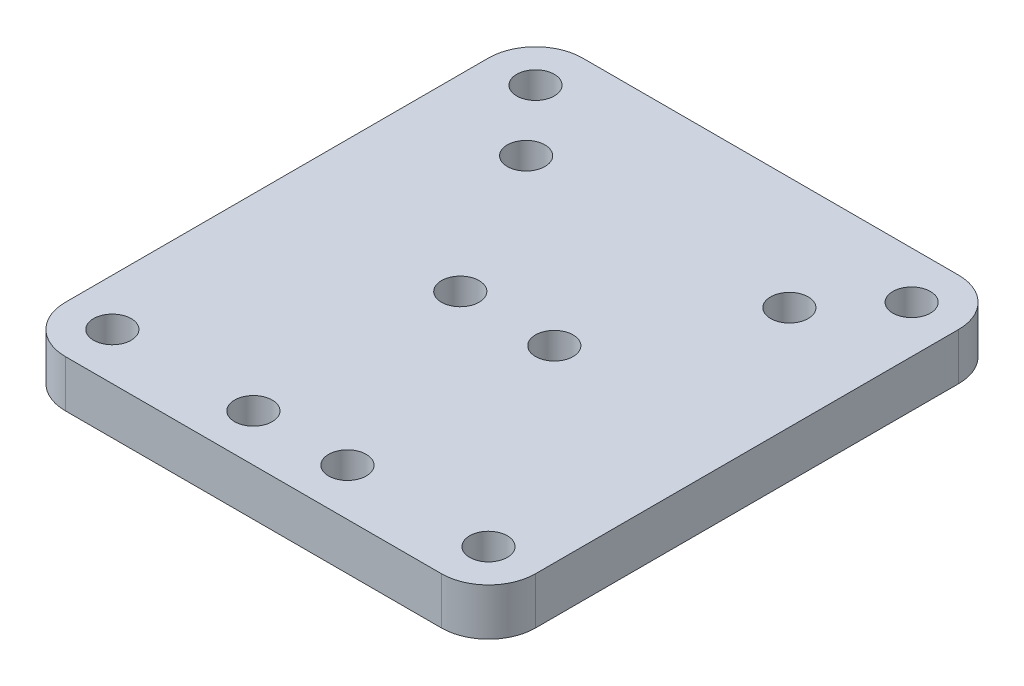
SolidWorks part; units mm, degrees
ref_plane "Plan de face" through (0, 0, 0) normal (0, 0, 1) x (1, 0, 0)
ref_plane "Plan de dessus" through (0, 0, 0) normal (0, 1, 0) x (1, 0, 0)
ref_plane "Plan de droite" through (0, 0, 0) normal (1, 0, 0) x (0, 0, -1)
sketch "Esquisse1" plane through (0, 0, 0) normal (0, 1, 0) x (1, 0, 0)
  line L0 (-62.6092, 0) -> (63.2078, 0) construction
  line L1 (25, -27.5) -> (-25, -27.5)
  line L2 (25, -27.5) -> (25, 27.5)
  line L3 (25, 27.5) -> (-25, 27.5)
  line L4 (-25, -27.5) -> (-25, 27.5)
  line L5 (25, -27.5) -> (-25, 27.5) construction
  line L6 (25, 27.5) -> (-25, -27.5) construction
  line L7 (-5, -22.5) -> (5, -22.5) construction
  line L8 (0, 21.3033) -> (0, -22.1041) construction
  line L11 (-5, 22.5) -> (5, 22.5) construction
  circle A0 centre (-5, -22.5) radius 2
  circle A1 centre (5, -22.5) radius 2
  circle A8 centre (-5, -0.5) radius 2
  circle A9 centre (5, -0.5) radius 2
  point P0 (0, 0)
  point P13 (0, 22.5)
  dimension "D1" = 55
  dimension "D3" = 4
  dimension "D4" = 4
  dimension "D7" = 4
  dimension "D8" = 4
  dimension "D2" = 50
  dimension "D5" = 10
  dimension "D6" = 5
  dimension "D9" = 22
extrude "Boss.-Extru.1" add sketch "Esquisse1" along normal blind 5
fillet "Congé1" radius 5 4 edges at (25, 2.5, 27.5) (25, 2.5, -27.5) (-25, 2.5, 27.5) (-25, 2.5, -27.5)
sketch "Esquisse2" plane through (0, 5, 0) normal (0, 1, 0) x (1, 0, 0)
  line L1 (-25, 0) -> (26.9694, 0) construction
  line L2 (-25, 22.5) -> (-25, -22.5) construction
  line L3 (20, 27.5) -> (-20, 27.5) construction
  line L4 (25, -22.5) -> (25, 22.5) construction
  circle A0 centre (-20, 22.5) radius 2
  circle A1 centre (-20, -22.5) radius 2
  circle A2 centre (20, -22.5) radius 2
  circle A3 centre (20, 22.5) radius 2
  circle A4 centre (-14, 15.5) radius 2
  circle A5 centre (14, 15.5) radius 2
  dimension "D1" = 4
  dimension "D2" = 4
  dimension "D3" = 4
  dimension "D4" = 4
  dimension "D5" = 4
  dimension "D6" = 4
  dimension "D7" = 12
  dimension "D8" = 11
  dimension "D9" = 12
  dimension "D10" = 11
extrude "Enlèv. mat.-Extru.1" cut sketch "Esquisse2" against normal blind 10
